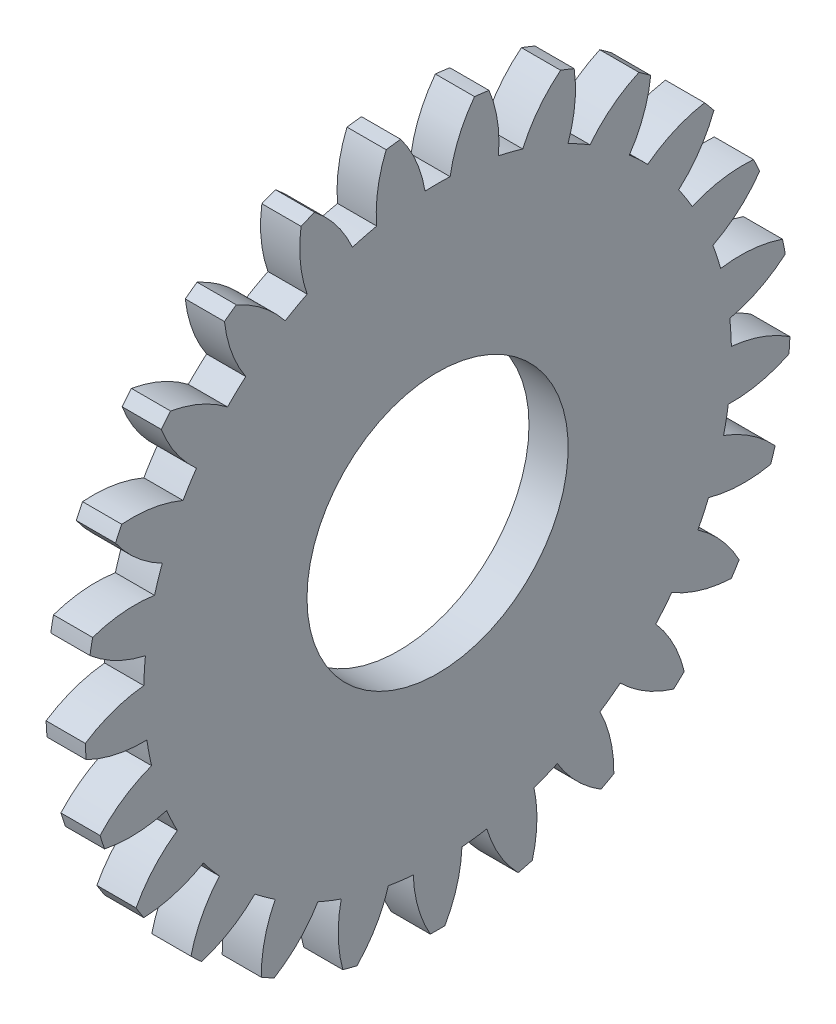
SolidWorks part; units mm, degrees
material "Zinc AC41A Alloy, As Cast"
ref_plane "Plane1" through (0, 0, 0) normal (0, 0, 1) x (1, 0, 0)
ref_plane "Plane2" through (0, 0, 0) normal (0, 1, 0) x (1, 0, 0)
ref_plane "Plane3" through (0, 0, 0) normal (1, 0, 0) x (0, 0, -1)
sketch "HoldingSke" plane through (0, 0, 0) normal (0, 1, 0) x (1, 0, 0)
  line L0 (0, 0) -> (0.9063, -0.4226)
  line L1 (-15, 0) -> (100, 0) construction
  line L2 (0, 0) -> (-2.1039, 2.3779)
  line L3 (0, 0) -> (-11.863, 4.5341)
  line L4 (0, 0) -> (7.8269, 3.6497)
  line L5 (0, 0) -> (-46.8476, -17.4728)
  line L6 (0, 0) -> (-1.2434, -0.839)
  line L7 (-2.1039, 2.3779) -> (8.6586, 51.2059)
  line L8 (-76.2, 54.61) -> (-74.4, 54.61)
  line L9 (-71.009, 38.7566) -> (-53.1078, 45.2721)
  line L10 (-76.2, 71.12) -> (104.1128, 71.12)
  line L11 (0, 0) -> (-1.5, 0)
  line L12 (-76.2, 101.6) -> (-76.162, 101.6)
  line L13 (24.9733, 27.94) -> (52.9518, 28.4284)
  line L14 (24.9733, 27.94) -> (24.9743, 27.94)
  line L15 (24.9733, 27.94) -> (100.4006, 29.5858)
  line L16 (-63.627, -1) -> (-12.827, -1)
  circle A0 centre (0, 0) radius 5
  circle A1 centre (0, 0) radius 11.249
  circle A2 centre (0, 0) radius 37.5
  circle A3 centre (0, 0) radius 5
  dimension "MHD" = 22.498
  dimension "Hub_dia" = 75
  dimension "Bore" = 10
  dimension "MBD" = 10
  dimension "Num_teeth" = 25
  dimension "Pitch" = 1
  dimension "Overall_len" = 50
  dimension "Show_teeth" = 25
  dimension "Thickness" = 1.5
  dimension "OAL" = 50.0001
  dimension "T_dim" = 1.8
  dimension "Ap" = 20
  dimension "H" = 19.05
  dimension "Pitch_radius" = 180.3128
  dimension "Width" = 1.5
  dimension "Backlash" = 0.038
  dimension "Addendum_fac" = 1
  dimension "Dedendum_fac" = 1.25
  dimension "Clearance_fac" = 0.25
  dimension "Dedendum_add" = 0.001
  dimension "Module" = 1
sketch "BasProSke" plane through (0, 0, 0) normal (0, 1, 0) x (1, 0, 0)
  line L0 (-10, 0) -> (60, 0) construction
  line L1 (0, 0) -> (0, 13.5)
  line L2 (0, 0) -> (1.5, 0)
  line L3 (1.5, 0) -> (1.5, 13.5)
  line L4 (1.5, 13.5) -> (0, 13.5)
  dimension "Thickness" = 1.5
  dimension "Diameter" = 27
revolve "Base-Revolve" add sketch "BasProSke" angle 360 about L0
sketch "TooCutSke" plane through (0, 0, 0) normal (1, 0, 0) x (0, 0, -1)
  line L1 (0, 0) -> (0, 107) construction
  line L2 (0, 0) -> (-0.8514, 12.471) construction
  line L3 (0, 0) -> (-3.1282, 24.7619) construction
  line L4 (-0.8514, 12.471) -> (-1.5641, 12.3809) construction
  arc A0 (0.4801, 11.2388) -> (-0.4801, 11.2388) centre (0, 0) ccw
  arc A1 (1.4322, 13.4494) -> (-1.4322, 13.4494) centre (0, 0) ccw
  circle A2 centre (0, 0) radius 12.5 construction
  circle A3 centre (0, 0) radius 11.7462 construction
  arc A4 (-0.4801, 11.2388) -> (-1.4322, 13.4494) centre (-5.4133, 10.4244) ccw
  arc A5 (1.4322, 13.4494) -> (0.4801, 11.2388) centre (5.4133, 10.4244) ccw
  dimension "Root_dia" = 22.498
  dimension "Overcut_dia" = 27.0508
  dimension "Pitch_dia" = 25
  dimension "Base_dia" = 23.4923
  dimension "Flank_rad" = 5
  dimension "Half_ang" = 7.2
  dimension "Half_CT" = 0.7184
extrude "ToothCut" cut sketch "TooCutSke" along normal through all
fillet "Breaks" [suppressed] radius 0.02
fillet "RootFillets" [suppressed] radius 0.251
pattern_circular "TeethCuts" count 25 every 14.4 about axis through (-10, 0, 0) along (1, 0, 0) of "ToothCut", "RootFillets", "Breaks"
sketch "HubNeaOneSke" plane through (0, 0, 0) normal (-1, 0, 0) x (0, 0, 1)
  circle A0 centre (0, 0) radius 11.249
  dimension "Diameter" = 22.498
extrude "HubNearOne" [suppressed] add sketch "HubNeaOneSke" along normal blind 48.5001
sketch "HubNeaBotSke" plane through (0, 0, 0) normal (-1, 0, 0) x (0, 0, 1)
  circle A0 centre (0, 0) radius 11.249
  dimension "Diameter" = 22.498
extrude "HubNearBoth" [suppressed] add sketch "HubNeaBotSke" along normal blind 24.25
ref_plane "FarPln" through (1.5, 0, 0) normal (1, 0, 0) x (0, 0, -1)
sketch "HubFarSke" plane through (1.5, 0, 0) normal (1, 0, 0) x (0, 0, -1)
  circle A0 centre (0, 0) radius 11.249
  dimension "Diameter" = 22.498
extrude "HubFar" [suppressed] add sketch "HubFarSke" along normal blind 24.25
sketch "BorSke" plane through (0, 0, 0) normal (1, 0, 0) x (0, 0, -1)
  circle A0 centre (0, 0) radius 5
  dimension "Diameter" = 10
extrude "Bore" cut sketch "BorSke" along normal mid plane 100.0001
sketch "KeySke" plane through (0, 0, 0) normal (1, 0, 0) x (0, 0, -1)
  line L0 (-1.5, 0) -> (-1.5, 6.8)
  line L1 (-1.5, 6.8) -> (1.5, 6.8)
  line L2 (1.5, 6.8) -> (1.5, 0)
  line L3 (0, 0) -> (0, 34) construction
  line L4 (-1.5, 0) -> (1.5, 0)
  dimension "Offset" = 6.8
  dimension "Width" = 3
extrude "Keyway" [suppressed] cut sketch "KeySke" along normal mid plane 100.0001
pattern_circular "Keyway2" [suppressed] count 2 every 90 about axis through (-10, 0, 0) along (1, 0, 0)
equation "' \"Module@HoldingSke\" = 6.35"
equation "' \"Num_teeth@HoldingSke\" = 12"
equation "' \"Ap@HoldingSke\" =  20"
equation "' \"Ap@HoldingSke\" = 20"
equation "' \"Width@HoldingSke\" = 0.5 * 25.4"
equation "' \"Hub_dia@HoldingSke\"= 1 * 25.4"
equation "' \"Hub_dia@HoldingSke\" = 1 * 25.4"
equation "' \"Overall_len@HoldingSke\" = 1.0 * 25.4"
equation "' \"Bore@HoldingSke\" = 0.75 * 25.4"
equation "' \"T_dim@HoldingSke\" = 0.1 * 25.4"
equation "' \"Width@KeySke\" = 0.25 * 25.4"
equation "' \"Show_teeth@HoldingSke\" = 13"
equation "' \"Backlash@HoldingSke\" = 0.009 * 25.4"
equation "' \"Addendum_fac@HoldingSke\" = 1.0"
equation "' \"Dedendum_fac@HoldingSke\" = 1.25"
equation "' \"Dedendum_add@HoldingSke\" = 0.00005 * 25.4"
equation "' \"Clearance_fac@HoldingSke\" = 0.25"
equation "\"Pitch@HoldingSke\" = 1 / \"Module@HoldingSke\""
equation "\"Overcut_dia@TooCutSke\" = (\"Num_teeth@HoldingSke\" + 2 * \"Addendum_fac@HoldingSke\") / \"Pitch@HoldingSke\" + 0.002 * 25.4"
equation "\"Pitch_dia@TooCutSke\" = \"Num_teeth@HoldingSke\" / \"Pitch@HoldingSke\""
equation "\"Base_dia@TooCutSke\" = \"Num_teeth@HoldingSke\" / \"Pitch@HoldingSke\" * cos((\"Ap@HoldingSke\"  * 3.14159265 / 180))"
equation "\"Root_dia@TooCutSke\" = (\"Num_teeth@HoldingSke\" + 2) / \"Pitch@HoldingSke\" - 2 * (\"Addendum_fac@HoldingSke\" + \"Dedendum_fac@HoldingSke\") / \"Pitch@HoldingSke\" - \"Dedendum_add@HoldingSke\" * 2"
equation "\"Half_ang@TooCutSke\" = 180 / \"Num_teeth@HoldingSke\""
equation "\"Half_CT@TooCutSke\" = \"Num_teeth@HoldingSke\" / \"Pitch@HoldingSke\" * sin((3.14159265 / 2 / \"Num_teeth@HoldingSke\")) / 2 - 7 * \"Backlash@HoldingSke\" / 4"
equation "\"Flank_rad@TooCutSke\" = \"Num_teeth@HoldingSke\" / \"Pitch@HoldingSke\" / 5"
equation "\"Radius@RootFillets\" = \"Clearance_fac@HoldingSke\" / \"Pitch@HoldingSke\" + \"Dedendum_add@HoldingSke\""
equation "\"Break_rad@Breaks\" = 0.02 / \"Pitch@HoldingSke\""
equation "\"Thickness@HoldingSke\" = \"Width@HoldingSke\""
equation "\"OAL@HoldingSke\" = \"Thickness@HoldingSke\""
equation "\"MHD@HoldingSke\" = (\"Num_teeth@HoldingSke\" + 2) / \"Pitch@HoldingSke\" - 2 * (\"Addendum_fac@HoldingSke\" + \"Dedendum_fac@HoldingSke\")  / \"Pitch@HoldingSke\" - \"Dedendum_add@HoldingSke\" * 2"
equation "\"MBD@HoldingSke\" = (\"Num_teeth@HoldingSke\" + 2) / \"Pitch@HoldingSke\" - 2 * (\"Addendum_fac@HoldingSke\" + \"Dedendum_fac@HoldingSke\")  / \"Pitch@HoldingSke\" - \"Dedendum_add@HoldingSke\" * 2 - 0.002 * 25.4"
equation "\"MHD@HoldingSke\" = ((sgn( \"MHD@HoldingSke\" - \"Hub_dia@HoldingSke\" )-1)*( \"MHD@HoldingSke\" - \"Hub_dia@HoldingSke\" ))/-2+ \"Hub_dia@HoldingSke\""
equation "\"MBD@HoldingSke\" = ((sgn( \"MBD@HoldingSke\" - \"Bore@HoldingSke\" )-1)*( \"MBD@HoldingSke\" - \"Bore@HoldingSke\" ))/-2+ \"Bore@HoldingSke\""
equation "\"OAL@HoldingSke\" = ((sgn( \"OAL@HoldingSke\" - \"Overall_len@HoldingSke\" )+1)*( \"OAL@HoldingSke\" - \"Overall_len@HoldingSke\" ))/2 + \"Overall_len@HoldingSke\" + 0.000002 * 25.4"
equation "\"Num_teeth@TeethCuts\" = int( \"Show_teeth@HoldingSke\" ) + 1"
equation "\"Num_teeth@TeethCuts\" = ((sgn( \"Num_teeth@TeethCuts\" - \"Num_teeth@HoldingSke\" )-1)*( \"Num_teeth@TeethCuts\" - \"Num_teeth@HoldingSke\" ))/-2+ \"Num_teeth@HoldingSke\""
equation "\"Num_teeth@TeethCuts\" = ((sgn( \"Num_teeth@TeethCuts\" - 2.0)+1)*( \"Num_teeth@TeethCuts\" - 2.0))/2 +2.0"
equation "\"Angle@TeethCuts\" = 360.0 / \"Num_teeth@HoldingSke\""
equation "\"Diameter@BasProSke\" = (\"Num_teeth@HoldingSke\" + 2 * \"Addendum_fac@HoldingSke\") / \"Pitch@HoldingSke\""
equation "\"Thickness@BasProSke\"  = \"Thickness@HoldingSke\""
equation "' \"Fillet_rad@BasProSke\" =  \"Thickness@HoldingSke\" * 0.05"
equation "' \"Fillet_rad@BasProSke\" = \"Thickness@HoldingSke\" * 0.05"
equation "\"MHD@HoldingSke\" = ((sgn( \"MHD@HoldingSke\" - \"Root_dia@TooCutSke\" )-1)*( \"MHD@HoldingSke\" - \"Root_dia@TooCutSke\" ))/-2+ \"Root_dia@TooCutSke\""
equation "\"Diameter@HubNeaOneSke\" = \"MHD@HoldingSke\""
equation "\"Length@HubNearOne\" = \"OAL@HoldingSke\" - \"Thickness@BasProSke\""
equation "\"Diameter@HubNeaBotSke\" = \"MHD@HoldingSke\""
equation "\"Length@HubNearBoth\" = ( \"OAL@HoldingSke\" - \"Thickness@BasProSke\" ) / 2.0"
equation "\"Thickness@FarPln\" = \"Thickness@BasProSke\""
equation "\"Diameter@HubFarSke\" = \"MHD@HoldingSke\""
equation "\"Length@HubFar\" = ( \"OAL@HoldingSke\" - \"Thickness@BasProSke\" ) / 2.0"
equation "\"Diameter@BorSke\" = \"MBD@HoldingSke\""
equation "\"D1@Bore\" = \"OAL@HoldingSke\" * 2.0"
equation "\"D1@Keyway\" = \"OAL@HoldingSke\" * 2.0"
equation "\"Offset@KeySke\" = \"T_dim@HoldingSke\" + \"MBD@HoldingSke\" / 2.0"
